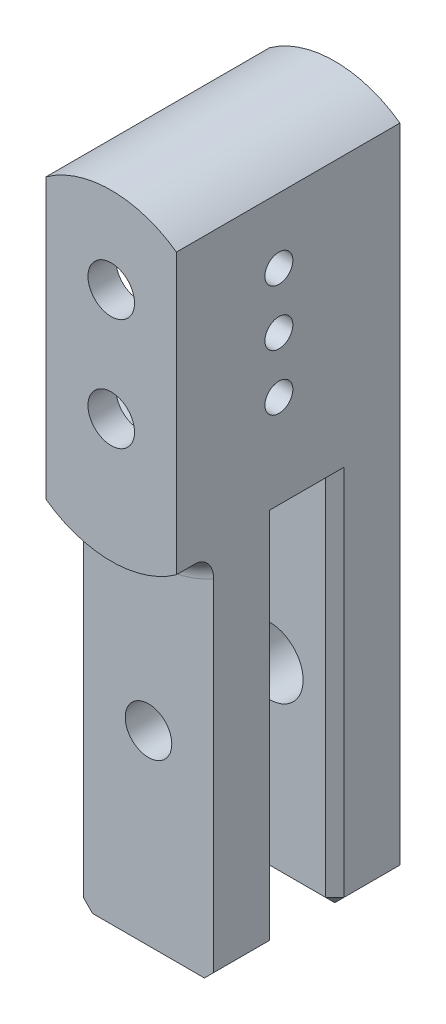
SolidWorks part; units mm, degrees
ref_plane "Front Plane" through (0, 0, 0) normal (0, 0, 1) x (1, 0, 0)
ref_plane "Top Plane" through (0, 0, 0) normal (0, 1, 0) x (1, 0, 0)
ref_plane "Right Plane" through (0, 0, 0) normal (1, 0, 0) x (0, 0, -1)
sketch "Sketch1" plane through (0, 0, 0) normal (0, 0, 1) x (1, 0, 0)
  line L1 (0, 0) -> (7, 0)
  line L2 (0, 0) -> (0, -35)
  line L3 (0, -35) -> (7, -35)
  line L4 (7, 0) -> (7, -35)
extrude "Boss-Extrude1" add sketch "Sketch1" along normal blind 3.5
sketch "Sketch2" plane through (0, 0, 3.5) normal (0, 0, 1) x (1, 0, 0)
  line L0 (0, 0) -> (0, -15)
  line L1 (0, 0) -> (0, -35) construction
  line L2 (0, -15) -> (7, -15)
  line L3 (7, -35) -> (7, 0) construction
  line L4 (7, -15) -> (7, 0)
  line L5 (7, 0) -> (0, 0)
extrude "Boss-Extrude2" add sketch "Sketch2" along normal blind 3
sketch "Sketch3" plane through (0, 0, 6.5) normal (0, 0, 1) x (1, 0, 0)
  line L1 (0, 0) -> (7, 0)
  line L2 (0, 0) -> (0, -35)
  line L3 (0, -35) -> (7, -35)
  line L4 (7, 0) -> (7, -35)
extrude "Boss-Extrude3" add sketch "Sketch3" along normal blind 3.5
sketch "Sketch4" plane through (0, 0, 10) normal (0, 0, 1) x (1, 0, 0)
  line L1 (0, 0) -> (7, 0)
  line L2 (0, 0) -> (0, -15)
  line L3 (0, -15) -> (7, -15)
  line L4 (7, 0) -> (7, -15)
extrude "Boss-Extrude4" add sketch "Sketch4" along normal blind 2
sketch "Sketch5" plane through (0, 0, 0) normal (-1, 0, 0) x (0, 0, 1)
  line L1 (3.5, -2) -> (10.5, -2)
  line L2 (3.5, -2) -> (3.5, -11)
  line L3 (3.5, -11) -> (10.5, -11)
  line L4 (10.5, -2) -> (10.5, -11)
  line L5 (12, 0) -> (0, 0) construction
  line L6 (12, 0) -> (12, -15) construction
  dimension "D1" = 9
  dimension "D2" = 7
  dimension "D3" = 1.5
  dimension "D4" = 2
extrude "Cut-Extrude1" cut sketch "Sketch5" against normal blind 5.5
sketch "Sketch6" plane through (5.5, 0, 0) normal (-1, 0, 0) x (0, 0, 1)
  line L0 (6.5, -2) -> (6.5, -11) construction
  line L1 (10.5, -2) -> (3.5, -2) construction
  line L2 (3.5, -11) -> (10.5, -11) construction
  line L3 (10.5, -11) -> (10.5, -2) construction
  line L4 (10.5, -2) -> (3.5, -2) construction
  circle A0 centre (6.5, -3.5) radius 0.75
  circle A1 centre (6.5, -9.5) radius 0.75
  circle A2 centre (6.5, -6.5) radius 0.75
  dimension "D2" = 1.5
  dimension "D4" = 4.5
  dimension "D1" = 4
  dimension "D3" = 1.5
extrude "Cut-Extrude2" cut sketch "Sketch6" against normal up to next
sketch "Sketch7" plane through (0, 0, 12) normal (0, 0, 1) x (1, 0, 0)
  line L0 (3.5, 0) -> (3.5, -15) construction
  line L1 (7, 0) -> (0, 0) construction
  line L2 (0, -15) -> (7, -15) construction
  line L3 (0, -2) -> (7, -2) construction
  line L4 (7, -15) -> (7, 0) construction
  circle A0 centre (3.5, -3.5) radius 1.25
  circle A1 centre (3.5, -9.5) radius 1.25
  dimension "D2" = 7.5
  dimension "D1" = 1.5
extrude "Cut-Extrude3" cut sketch "Sketch7" against normal up to next
sketch "Sketch9" plane through (0, 0, 12) normal (0, 0, 1) x (1, 0, 0)
  line L0 (0, 0) -> (7, 0)
  arc A0 (7, 0) -> (0, 0) centre (3.5, -4.8734) ccw
extrude "Boss-Extrude5" add sketch "Sketch9" against normal up to surface (12 mm away) up to face at (3.5, -17.5, 0)
sketch "Sketch10" plane through (0, 0, 12) normal (0, 0, 1) x (1, 0, 0)
  line L0 (0, -15) -> (7, -15)
  arc A0 (0, -15) -> (7, -15) centre (3.5, -10.1266) ccw
extrude "Boss-Extrude6" add sketch "Sketch10" against normal up to surface (2 mm away) up to face at (3.5, -25, 10)
chamfer "Chamfer1" distance 0.5 angle 45 12 edges at (0, -25, 3.5) (0, -15, 5) (0, -25, 6.5) (7, -35, 8.25) (0, -35, 8.25) (3.5, -35, 6.5) (0, -35, 1.75) (3.5, -35, 3.5) (7, -35, 1.75) (7, -25, 6.5) (7, -25, 3.5) (7, -15, 5)
sketch "Sketch11" plane through (0, 0, 10) normal (0, 0, 1) x (1, 0, 0)
  line L0 (3.5, -35) -> (3.5, -16.1266) construction
  line L1 (0.5, -35) -> (6.5, -35) construction
  arc A0 (0, -15) -> (7, -15) centre (3.5, -10.1266) ccw construction
  circle A1 centre (3.5, -25) radius 1.25
  dimension "D1" = 10
extrude "Cut-Extrude4" cut sketch "Sketch11" against normal up to next
sketch "Sketch12" plane through (0, 0, 0) normal (0, 0, -1) x (-1, 0, 0)
  line L0 (-3.5, -35) -> (-3.5, -18.8417) construction
  line L1 (-0.5, -35) -> (-6.5, -35) construction
  circle A0 centre (-3.5, -25) radius 1.8
  dimension "D1" = 10
extrude "Cut-Extrude5" cut sketch "Sketch12" against normal up to next
fillet "Fillet1" radius 1 1 edges at (3.5, -16.1266, 10)
